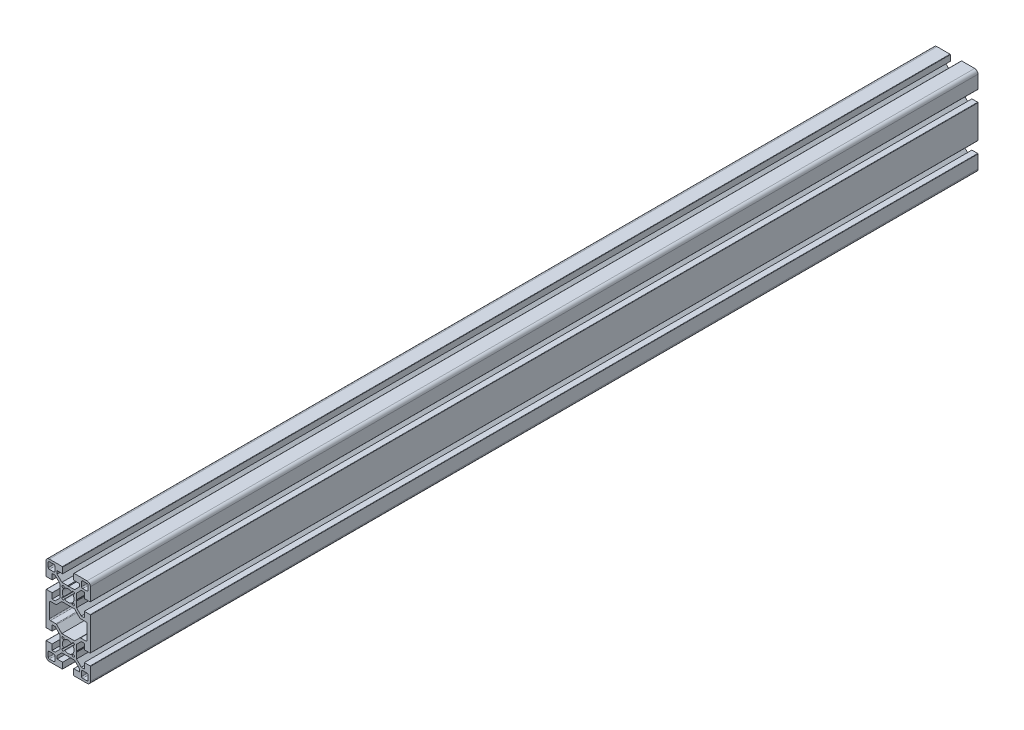
SolidWorks part; units mm, degrees
ref_plane "Front Plane" through (0, 0, 0) normal (0, 0, 1) x (1, 0, 0)
ref_plane "Top Plane" through (0, 0, 0) normal (0, 1, 0) x (1, 0, 0)
ref_plane "Right Plane" through (0, 0, 0) normal (1, 0, 0) x (0, 0, -1)
sketch "Sketch3" plane through (0, 0, 0) normal (0, 0, 1) x (1, 0, 0)
  line L0 (-17, -40) -> (-5.3, -40)
  line L1 (-5, -39.7) -> (-5, -34.5)
  line L2 (-5, -34.5) -> (-10, -34.5)
  line L3 (-10, -34.5) -> (-10, -31.7678)
  line L4 (-10, -31.7678) -> (-5.7322, -27.5)
  line L5 (-5.7322, -27.5) -> (-0.5196, -27.5)
  line L6 (-0.5196, -27.5) -> (0, -27.2)
  line L7 (0, -27.2) -> (0.5196, -27.5)
  line L8 (0.5196, -27.5) -> (5.7322, -27.5)
  line L9 (5.7322, -27.5) -> (10, -31.7678)
  line L10 (10, -31.7678) -> (10, -34.5)
  line L11 (10, -34.5) -> (5, -34.5)
  line L12 (5, -34.5) -> (5, -39.7)
  line L13 (5.3, -40) -> (17, -40)
  line L14 (20, -37) -> (20, -25.3)
  line L15 (19.7, -25) -> (14.5, -25)
  line L16 (14.5, -25) -> (14.5, -30)
  line L17 (14.5, -30) -> (11.7678, -30)
  line L18 (11.7678, -30) -> (7.5, -25.7322)
  line L19 (7.5, -25.7322) -> (7.5, -20.5196)
  line L20 (7.5, -20.5196) -> (7.2, -20)
  line L21 (7.2, -20) -> (7.5, -19.4804)
  line L22 (7.5, -19.4804) -> (7.5, -14.2678)
  line L23 (7.5, -14.2678) -> (11.7678, -10)
  line L24 (11.7678, -10) -> (14.5, -10)
  line L25 (14.5, -10) -> (14.5, -15)
  line L26 (14.5, -15) -> (19.7, -15)
  line L27 (20, -14.7) -> (20, 14.7)
  line L28 (19.7, 15) -> (14.5, 15)
  line L29 (14.5, 15) -> (14.5, 10)
  line L30 (14.5, 10) -> (11.7678, 10)
  line L31 (11.7678, 10) -> (7.5, 14.2678)
  line L32 (7.5, 14.2678) -> (7.5, 19.4804)
  line L33 (7.5, 19.4804) -> (7.2, 20)
  line L34 (7.2, 20) -> (7.5, 20.5196)
  line L35 (7.5, 20.5196) -> (7.5, 25.7322)
  line L36 (7.5, 25.7322) -> (11.7678, 30)
  line L37 (11.7678, 30) -> (14.5, 30)
  line L38 (14.5, 30) -> (14.5, 25)
  line L39 (14.5, 25) -> (19.7, 25)
  line L40 (20, 25.3) -> (20, 37)
  line L41 (17, 40) -> (5.3, 40)
  line L42 (5, 39.7) -> (5, 34.5)
  line L43 (5, 34.5) -> (10, 34.5)
  line L44 (10, 34.5) -> (10, 31.7678)
  line L45 (10, 31.7678) -> (5.7322, 27.5)
  line L46 (5.7322, 27.5) -> (0.5196, 27.5)
  line L47 (0.5196, 27.5) -> (0, 27.2)
  line L48 (0, 27.2) -> (-0.5196, 27.5)
  line L49 (-0.5196, 27.5) -> (-5.7322, 27.5)
  line L50 (-5.7322, 27.5) -> (-10, 31.7678)
  line L51 (-10, 31.7678) -> (-10, 34.5)
  line L52 (-10, 34.5) -> (-5, 34.5)
  line L53 (-5, 34.5) -> (-5, 39.7)
  line L54 (-5.3, 40) -> (-17, 40)
  line L55 (-20, 37) -> (-20, 25.3)
  line L56 (-19.7, 25) -> (-14.5, 25)
  line L57 (-14.5, 25) -> (-14.5, 30)
  line L58 (-14.5, 30) -> (-11.7678, 30)
  line L59 (-11.7678, 30) -> (-7.5, 25.7322)
  line L60 (-7.5, 25.7322) -> (-7.5, 20.5196)
  line L61 (-7.5, 20.5196) -> (-7.2, 20)
  line L62 (-7.2, 20) -> (-7.5, 19.4804)
  line L63 (-7.5, 19.4804) -> (-7.5, 14.2678)
  line L64 (-7.5, 14.2678) -> (-11.7678, 10)
  line L65 (-11.7678, 10) -> (-14.5, 10)
  line L66 (-14.5, 10) -> (-14.5, 15)
  line L67 (-14.5, 15) -> (-19.7, 15)
  line L68 (-20, 14.7) -> (-20, -14.7)
  line L69 (-19.7, -15) -> (-14.5, -15)
  line L70 (-14.5, -15) -> (-14.5, -10)
  line L71 (-14.5, -10) -> (-11.7678, -10)
  line L72 (-11.7678, -10) -> (-7.5, -14.2678)
  line L73 (-7.5, -14.2678) -> (-7.5, -19.4804)
  line L74 (-7.5, -19.4804) -> (-7.2, -20)
  line L75 (-7.2, -20) -> (-7.5, -20.5196)
  line L76 (-7.5, -20.5196) -> (-7.5, -25.7322)
  line L77 (-7.5, -25.7322) -> (-11.7678, -30)
  line L78 (-11.7678, -30) -> (-14.5, -30)
  line L79 (-14.5, -30) -> (-14.5, -25)
  line L80 (-14.5, -25) -> (-19.7, -25)
  line L81 (-20, -25.3) -> (-20, -37)
  line L82 (12, -33) -> (12, -37)
  line L83 (13, -38) -> (17, -38)
  line L84 (18, -37) -> (18, -33)
  line L85 (17, -32) -> (13, -32)
  line L86 (12, 37) -> (12, 33)
  line L87 (13, 32) -> (17, 32)
  line L88 (18, 33) -> (18, 37)
  line L89 (17, 38) -> (13, 38)
  line L90 (-16, -7.5) -> (-11.1464, -7.5)
  line L91 (-10.4393, -7.7929) -> (-5.7322, -12.5)
  line L92 (-5.7322, -12.5) -> (5.7322, -12.5)
  line L93 (5.7322, -12.5) -> (10.4393, -7.7929)
  line L94 (11.1464, -7.5) -> (16, -7.5)
  line L95 (17, -6.5) -> (17, 6.5)
  line L96 (16, 7.5) -> (11.1464, 7.5)
  line L97 (10.4393, 7.7929) -> (5.7322, 12.5)
  line L98 (5.7322, 12.5) -> (-5.7322, 12.5)
  line L99 (-5.7322, 12.5) -> (-10.4394, 7.7929)
  line L100 (-11.1465, 7.5) -> (-16, 7.5)
  line L101 (-17, 6.5) -> (-17, -6.5)
  line L102 (-18, 37) -> (-18, 33)
  line L103 (-17, 32) -> (-13, 32)
  line L104 (-12, 33) -> (-12, 37)
  line L105 (-13, 38) -> (-17, 38)
  line L106 (-18, -33) -> (-18, -37)
  line L107 (-17, -38) -> (-13, -38)
  line L108 (-12, -37) -> (-12, -33)
  line L109 (-13, -32) -> (-17, -32)
  arc A0 (-20, -37) -> (-17, -40) centre (-17, -37) ccw
  arc A1 (-5.3, -40) -> (-5, -39.7) centre (-5.3, -39.7) ccw
  arc A2 (5, -39.7) -> (5.3, -40) centre (5.3, -39.7) ccw
  arc A3 (17, -40) -> (20, -37) centre (17, -37) ccw
  arc A4 (20, -25.3) -> (19.7, -25) centre (19.7, -25.3) ccw
  arc A5 (19.7, -15) -> (20, -14.7) centre (19.7, -14.7) ccw
  arc A6 (20, 14.7) -> (19.7, 15) centre (19.7, 14.7) ccw
  arc A7 (19.7, 25) -> (20, 25.3) centre (19.7, 25.3) ccw
  arc A8 (20, 37) -> (17, 40) centre (17, 37) ccw
  arc A9 (5.3, 40) -> (5, 39.7) centre (5.3, 39.7) ccw
  arc A10 (-5, 39.7) -> (-5.3, 40) centre (-5.3, 39.7) ccw
  arc A11 (-17, 40) -> (-20, 37) centre (-17, 37) ccw
  arc A12 (-20, 25.3) -> (-19.7, 25) centre (-19.7, 25.3) ccw
  arc A13 (-19.7, 15) -> (-20, 14.7) centre (-19.7, 14.7) ccw
  arc A14 (-20, -14.7) -> (-19.7, -15) centre (-19.7, -14.7) ccw
  arc A15 (-19.7, -25) -> (-20, -25.3) centre (-19.7, -25.3) ccw
  arc A16 (12, -37) -> (13, -38) centre (13, -37) ccw
  arc A17 (17, -38) -> (18, -37) centre (17, -37) ccw
  arc A18 (18, -33) -> (17, -32) centre (17, -33) ccw
  arc A19 (13, -32) -> (12, -33) centre (13, -33) ccw
  arc A20 (12, 33) -> (13, 32) centre (13, 33) ccw
  arc A21 (17, 32) -> (18, 33) centre (17, 33) ccw
  arc A22 (18, 37) -> (17, 38) centre (17, 37) ccw
  arc A23 (13, 38) -> (12, 37) centre (13, 37) ccw
  arc A24 (-3.5963, 24.608) -> (-4.6065, 23.5962) centre (-4.5962, 24.5962) ccw
  arc A25 (-4.6065, 23.5962) -> (-4.3061, 23.0033) centre (-4.6221, 23.2158) cw
  arc A26 (-4.3061, 23.0033) -> (-4.3062, 16.9968) centre (0, 20) ccw
  arc A27 (-4.3062, 16.9968) -> (-4.6058, 16.4038) centre (-4.6222, 16.7842) cw
  arc A28 (-4.6058, 16.4038) -> (-3.5962, 15.3944) centre (-4.5962, 15.4038) ccw
  arc A29 (-3.5962, 15.3944) -> (-3.0035, 15.694) centre (-3.2158, 15.3778) cw
  arc A30 (-3.0035, 15.694) -> (3.0034, 15.694) centre (0, 20) ccw
  arc A31 (3.0034, 15.694) -> (3.5962, 15.3939) centre (3.2158, 15.3778) cw
  arc A32 (3.5962, 15.3939) -> (4.6058, 16.4038) centre (4.5962, 15.4038) ccw
  arc A33 (4.6058, 16.4038) -> (4.3071, 16.9981) centre (4.6221, 16.7842) cw
  arc A34 (4.3071, 16.9981) -> (4.3057, 23.0039) centre (0, 20) ccw
  arc A35 (4.3057, 23.0039) -> (4.6058, 23.5962) centre (4.6222, 23.2158) cw
  arc A36 (4.6058, 23.5962) -> (3.5962, 24.6061) centre (4.5962, 24.5962) ccw
  arc A37 (3.5962, 24.6061) -> (3.0033, 24.3061) centre (3.2158, 24.6222) cw
  arc A38 (3.0033, 24.3061) -> (-3.0034, 24.3061) centre (0, 20) ccw
  arc A39 (-3.0034, 24.3061) -> (-3.5963, 24.608) centre (-3.2158, 24.6221) cw
  arc A40 (-3.5963, -15.392) -> (-4.6065, -16.4038) centre (-4.5962, -15.4038) ccw
  arc A41 (-4.6065, -16.4038) -> (-4.3061, -16.9967) centre (-4.6221, -16.7842) cw
  arc A42 (-4.3061, -16.9967) -> (-4.3062, -23.0032) centre (0, -20) ccw
  arc A43 (-4.3062, -23.0032) -> (-4.6058, -23.5962) centre (-4.6222, -23.2158) cw
  arc A44 (-4.6058, -23.5962) -> (-3.5962, -24.6056) centre (-4.5962, -24.5962) ccw
  arc A45 (-3.5962, -24.6056) -> (-3.0035, -24.306) centre (-3.2158, -24.6222) cw
  arc A46 (-3.0035, -24.306) -> (3.0034, -24.306) centre (0, -20) ccw
  arc A47 (3.0034, -24.306) -> (3.5962, -24.6061) centre (3.2158, -24.6222) cw
  arc A48 (3.5962, -24.6061) -> (4.6058, -23.5962) centre (4.5962, -24.5962) ccw
  arc A49 (4.6058, -23.5962) -> (4.3071, -23.0019) centre (4.6221, -23.2158) cw
  arc A50 (4.3071, -23.0019) -> (4.3057, -16.9961) centre (0, -20) ccw
  arc A51 (4.3057, -16.9961) -> (4.6058, -16.4038) centre (4.6222, -16.7842) cw
  arc A52 (4.6058, -16.4038) -> (3.5962, -15.3939) centre (4.5962, -15.4038) ccw
  arc A53 (3.5962, -15.3939) -> (3.0033, -15.6939) centre (3.2158, -15.3778) cw
  arc A54 (3.0033, -15.6939) -> (-3.0034, -15.6939) centre (0, -20) ccw
  arc A55 (-3.0034, -15.6939) -> (-3.5963, -15.392) centre (-3.2158, -15.3779) cw
  arc A56 (-17, -6.5) -> (-16, -7.5) centre (-16, -6.5) ccw
  arc A57 (-11.1464, -7.5) -> (-10.4393, -7.7929) centre (-11.1464, -8.5) cw
  arc A58 (10.4393, -7.7929) -> (11.1464, -7.5) centre (11.1464, -8.5) cw
  arc A59 (16, -7.5) -> (17, -6.5) centre (16, -6.5) ccw
  arc A60 (17, 6.5) -> (16, 7.5) centre (16, 6.5) ccw
  arc A61 (11.1464, 7.5) -> (10.4393, 7.7929) centre (11.1464, 8.5) cw
  arc A62 (-10.4394, 7.7929) -> (-11.1465, 7.5) centre (-11.1465, 8.5) cw
  arc A63 (-16, 7.5) -> (-17, 6.5) centre (-16, 6.5) ccw
  arc A64 (-18, 33) -> (-17, 32) centre (-17, 33) ccw
  arc A65 (-13, 32) -> (-12, 33) centre (-13, 33) ccw
  arc A66 (-12, 37) -> (-13, 38) centre (-13, 37) ccw
  arc A67 (-17, 38) -> (-18, 37) centre (-17, 37) ccw
  arc A68 (-18, -37) -> (-17, -38) centre (-17, -37) ccw
  arc A69 (-13, -38) -> (-12, -37) centre (-13, -37) ccw
  arc A70 (-12, -33) -> (-13, -32) centre (-13, -33) ccw
  arc A71 (-17, -32) -> (-18, -33) centre (-17, -33) ccw
extrude "Boss-Extrude1" add sketch "Sketch3" along normal blind 800
